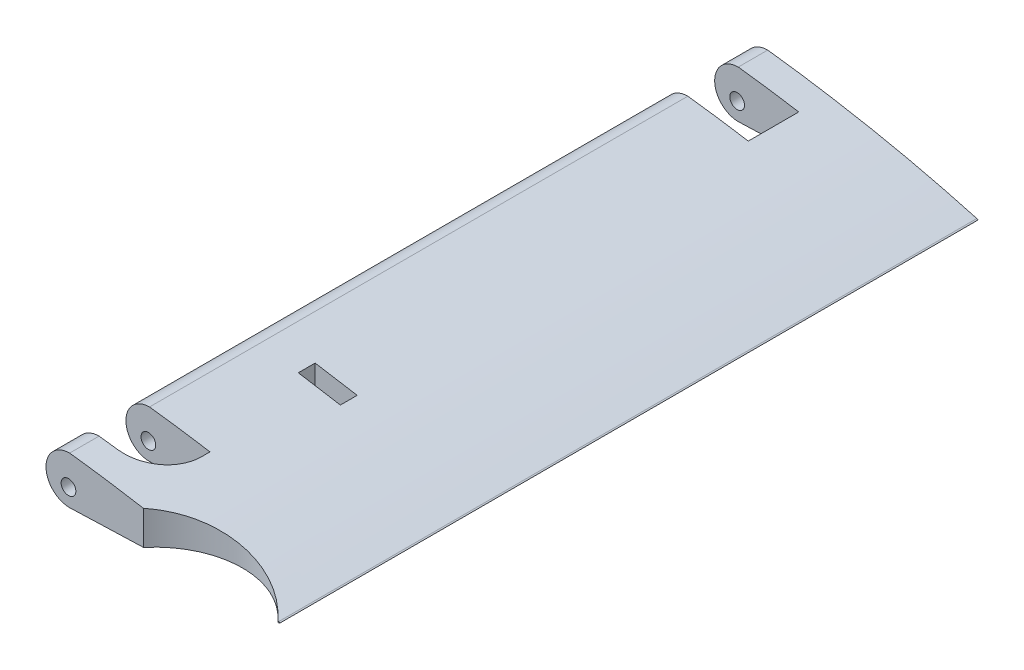
SolidWorks part; units mm, degrees
material "Balsa"
ref_plane "Front Plane" through (0, 0, 0) normal (0, 0, 1) x (1, 0, 0)
ref_plane "Top Plane" through (0, 0, 0) normal (0, 1, 0) x (1, 0, 0)
ref_plane "Right Plane" through (0, 0, 0) normal (1, 0, 0) x (0, 0, -1)
curve "曲線2"
  spline degree 3 poles (200, 0.26, 0) (196.6701, 1.1665, 0) (190.0264, 2.975, 0) (176.7171, 6.2635, 0) (160.0733, 9.8968, 0) (140.0541, 13.4784, 0) (120.0503, 16.4141, 0) (100.0354, 18.5082, 0) (80.0223, 19.8143, 0) (63.3151, 19.8275, 0) (49.9753, 18.9046, 0) (39.957, 17.689, 0) (29.917, 15.8963, 0) (21.5972, 13.7404, 0) (14.9301, 11.563, 0) (9.903, 9.5074, 0) (5.6136, 7.2843, 0) (1.8903, 4.6252, 0) (-1.3508, 0.3484, 0) (2.1476, -2.9224, 0) (5.7173, -4.2063, 0) (9.9686, -5.0729, 0) (14.9893, -5.5135, 0) (21.6639, -5.8253, 0) (30.0021, -5.8019, 0) (40.0043, -5.522, 0) (49.9995, -4.9891, 0) (63.3329, -4.3655, 0) (79.9968, -3.5653, 0) (100.0006, -2.8138, 0) (119.9979, -1.9794, 0) (139.9972, -1.2688, 0) (159.998, -0.746, 0) (176.6662, -0.4806, 0) (189.9997, -0.3058, 0) (196.6666, -0.2753, 0) (200, -0.26, 0) knots 0 0 0 0 0.025305 0.050488 0.10052 0.150191 0.199587 0.24874 0.297716 0.346601 0.371103 0.395726 0.42057 0.445825 0.458702 0.47192 0.485786 0.493461 0.506863 0.516148 0.522766 0.535269 0.547551 0.559786 0.584229 0.608681 0.633151 0.657622 0.706558 0.755482 0.804406 0.85332 0.902221 0.951113 0.975557 1 1 1 1
sketch "草圖4" plane through (0, 0, 0) normal (0, 0, 1) x (1, 0, 0)
  line L8 (26.3929, -5.7959) -> (118.9885, -5.7959) construction
  spline S1 degree 2 poles (120, 0.156) (120.5501, 0) (120, -0.156) knots 0 0 0 1 1 1
  spline S2 degree 3 poles (120, 0.156) (118.0021, 0.6999) (114.0158, 1.785) (106.0302, 3.7581) (96.044, 5.9381) (84.0324, 8.087) (72.0302, 9.8485) (60.0213, 11.1049) (48.0134, 11.8886) (37.9891, 11.8965) (29.9852, 11.3428) (23.9742, 10.6134) (17.9502, 9.5378) (12.9583, 8.2442) (8.9581, 6.9378) (5.9418, 5.7044) (3.3681, 4.3706) (1.1342, 2.7751) (-0.8105, 0.209) (1.2885, -1.7534) (3.4304, -2.5238) (5.9811, -3.0437) (8.9936, -3.3081) (12.9983, -3.4952) (18.0013, -3.4812) (24.0026, -3.3132) (29.9997, -2.9935) (37.9998, -2.6193) (47.9981, -2.1392) (60.0003, -1.6883) (71.9988, -1.1877) (83.9983, -0.7613) (95.9988, -0.4476) (105.9997, -0.2883) (113.9998, -0.1835) (118, -0.1652) (120, -0.156) knots 0 0 0 0 0.025305 0.050488 0.10052 0.150191 0.199587 0.24874 0.297716 0.346601 0.371103 0.395726 0.42057 0.445825 0.458702 0.47192 0.485786 0.493461 0.506863 0.516148 0.522766 0.535269 0.547551 0.559786 0.584229 0.608681 0.633151 0.657622 0.706558 0.755482 0.804406 0.85332 0.902221 0.951113 0.975557 1 1 1 1
extrude "填料-伸長1" add sketch "草圖4" along normal blind 185
sketch "草圖2" plane through (0, 0, 0) normal (0, 0, -1) x (-1, 0, 0)
  circle A0 centre (-25, 5) radius 3.25
  circle A1 centre (-50, 5) radius 3.25
  dimension "D1" = 6.5
  dimension "D2" = 25
  dimension "D3" = 25
  dimension "D4" = 5
extrude "除料-伸長1" cut sketch "草圖2" against normal through all
sketch "草圖3" plane through (0, 0, 0) normal (0, 1, 0) x (1, 0, 0)
  line L0 (120, 0) -> (-0.0337, 0) construction
  line L1 (70.275, -12) -> (120.275, -12)
  line L2 (70.275, -12) -> (70.275, -178)
  line L3 (70.275, -178) -> (120.275, -178)
  line L6 (-0.0337, -185) -> (120, -185) construction
  line L16 (120.275, -12) -> (166.4805, 19.3533)
  line L17 (166.4805, 19.3533) -> (-21.7711, 70.9334)
  line L18 (-21.7711, 70.9334) -> (-60.7316, -48.3616)
  line L19 (-60.7316, -48.3616) -> (-45.0232, -192.445)
  line L20 (-45.0232, -192.445) -> (84.8579, -230.5752)
  line L21 (84.8579, -230.5752) -> (139.8603, -200.5385)
  line L22 (139.8603, -200.5385) -> (120.275, -178)
  dimension "D1" = 12
  dimension "D3" = 7
extrude "除料-伸長2" cut sketch "草圖3" against normal through all and the other way through all
sketch "草圖5" plane through (0, 0, 178) normal (0, 0, 1) x (1, 0, 0)
  line L0 (70.275, 9.9794) -> (70.275, -1.2673)
  arc A0 (70.275, 9.9794) -> (70.275, -1.2673) centre (70.275, 4.356) ccw
extrude "填料-伸長2" add sketch "草圖5" against normal through all
sketch "草圖6" plane through (0, 0, 178) normal (0, 0, 1) x (1, 0, 0)
  circle A0 centre (70, 2.844) radius 1.75
  dimension "D1" = 3.5
  dimension "D2" = 50
  dimension "D3" = 3
extrude "除料-伸長3" cut sketch "草圖6" against normal through all
sketch "草圖7" plane through (0, 0, 0) normal (0, 1, 0) x (1, 0, 0)
  line L0 (120, -12) -> (70.275, -12) construction
  line L1 (79.6516, -57) -> (89.6516, -57)
  line L2 (79.6516, -57) -> (79.6516, -61)
  line L3 (79.6516, -61) -> (89.6516, -61)
  line L4 (89.6516, -57) -> (89.6516, -61)
  line L5 (64.6516, -12) -> (64.6516, -178) construction
  line L6 (70.275, -178) -> (120, -178) construction
  line L7 (64.6516, -19) -> (84.6516, -19)
  line L8 (64.6516, -19) -> (64.6516, -31)
  line L9 (64.6516, -31) -> (84.6516, -31)
  line L10 (84.6516, -19) -> (84.6516, -31)
  line L11 (64.6516, -171) -> (84.6516, -171)
  line L12 (64.6516, -171) -> (64.6516, -159)
  line L13 (64.6516, -159) -> (84.6516, -159)
  line L14 (84.6516, -171) -> (84.6516, -159)
  dimension "D1" = 4
  dimension "D2" = 10
  dimension "D3" = 45
  dimension "D4" = 25
  dimension "D5" = 20
  dimension "D6" = 7
  dimension "D7" = 7
  dimension "D8" = 12
extrude "除料-伸長4" cut sketch "草圖7" against normal through all and the other way through all
sketch "草圖9" plane through (0, 0, 0) normal (0, 1, 0) x (1, 0, 0)
  circle A0 centre (103.803, 2.085) radius 21.2881
extrude "除料-伸長6" cut sketch "草圖9" against normal through all and the other way through all
fillet "圓角1" radius 10 1 edges at (84.6516, 3.5807, 19)
mirror "鏡射1" about plane through (70.275, -3.4952, 12) normal (0, 0, 1) of bodies 179
sketch "草圖10" plane through (0, 0, 0) normal (0, 1, 0) x (1, 0, 0)
  line L1 (27.2247, -12) -> (159.0873, -12)
  line L2 (27.2247, -12) -> (27.2247, -183.3307)
  line L3 (27.2247, -183.3307) -> (159.0873, -183.3307)
  line L4 (159.0873, -12) -> (159.0873, -183.3307)
extrude "除料-伸長7" cut sketch "草圖10" against normal through all and the other way through all
